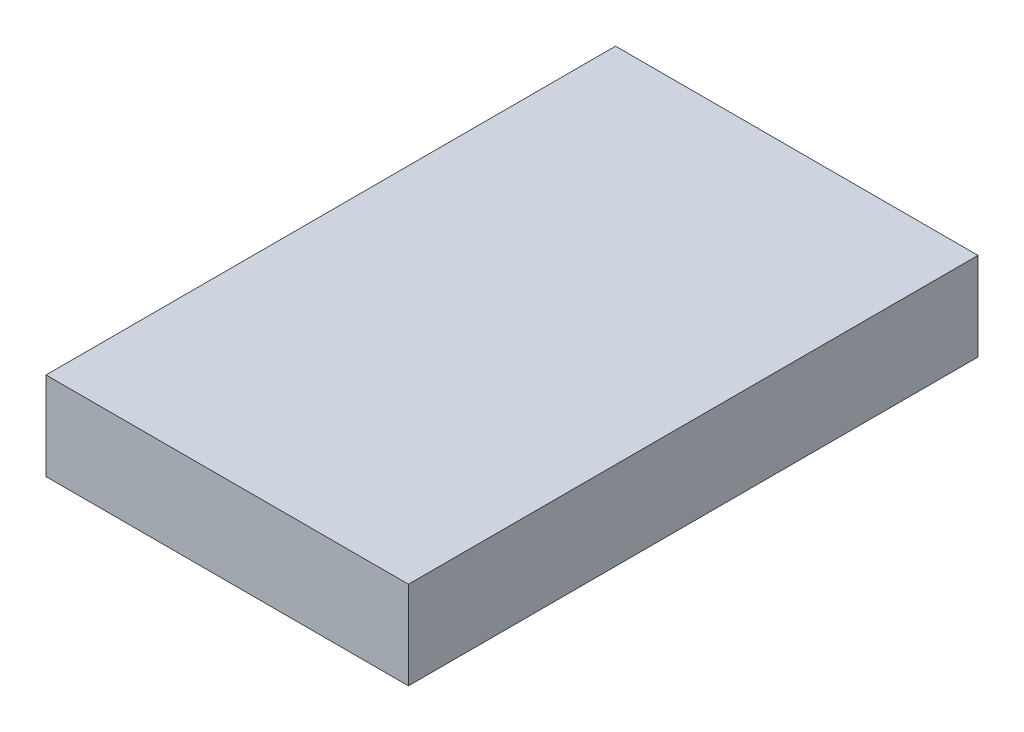
SolidWorks part; units mm, degrees
ref_plane "Plano frontal" through (0, 0, 0) normal (0, 0, 1) x (1, 0, 0)
ref_plane "Plano superior" through (0, 0, 0) normal (0, 1, 0) x (1, 0, 0)
ref_plane "Plano direito" through (0, 0, 0) normal (1, 0, 0) x (0, 0, -1)
ref_plane "Plano1" through (0, 17, 0) normal (0, 1, 0) x (1, 0, 0)
sketch "Esboço1" plane through (0, 17, 0) normal (0, 1, 0) x (1, 0, 0)
  line L0 (0, 110) -> (0, 0)
  line L1 (0, 0) -> (70, 0)
  line L2 (70, 0) -> (70, 110)
  line L3 (70, 110) -> (0, 110)
extrude "Ressalto-extrusão1" add sketch "Esboço1" against normal blind 17
